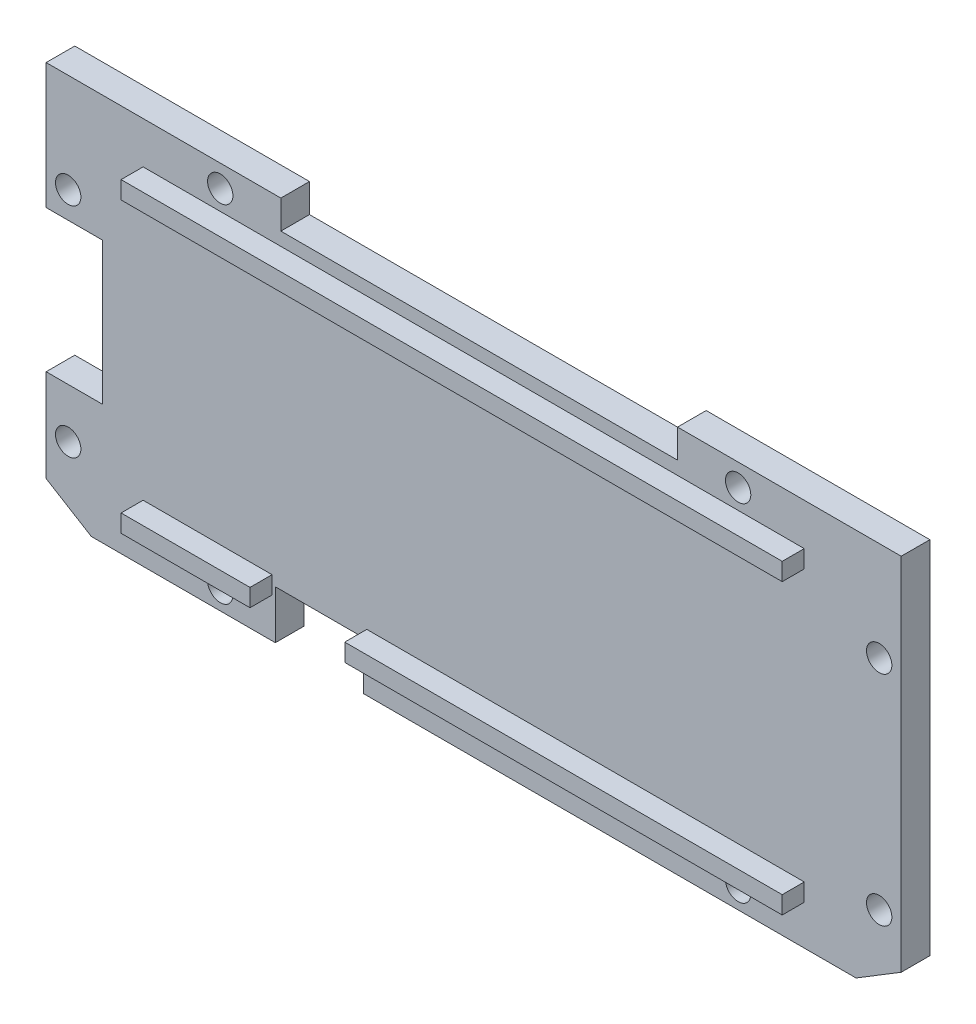
SolidWorks part; units mm, degrees
ref_plane "前视基准面" through (0, 0, 0) normal (0, 0, 1) x (1, 0, 0)
ref_plane "上视基准面" through (0, 0, 0) normal (0, 1, 0) x (1, 0, 0)
ref_plane "右视基准面" through (0, 0, 0) normal (1, 0, 0) x (0, 0, -1)
other "Configuration Table"
sketch "Trimmed upper shelf - cable notch and antenna relief profile" plane through (0, 0, 0) normal (0, 0, 1) x (1, 0, 0)
  line L0 (-38.8, -21.5) -> (-34.7, -24)
  line L1 (-34.7, -24) -> (-18, -24)
  line L2 (-18, -24) -> (-18, -19.6)
  line L3 (-18, -19.6) -> (-10, -19.6)
  line L4 (-10, -19.6) -> (-10, -24)
  line L5 (-10, -24) -> (34.7, -24)
  line L6 (34.7, -24) -> (38.8, -21.5)
  line L7 (38.8, -21.5) -> (38.8, 11.2)
  line L8 (38.8, 11.2) -> (18.5, 11.2)
  line L9 (18.5, 11.2) -> (18.5, 8.6)
  line L10 (18.5, 8.6) -> (-17.5, 8.6)
  line L11 (-17.5, 8.6) -> (-17.5, 11.2)
  line L12 (-17.5, 11.2) -> (-38.8, 11.2)
  line L13 (-38.8, 11.2) -> (-38.8, -0.2)
  line L14 (-38.8, -0.2) -> (-33.7, -0.2)
  line L15 (-33.7, -0.2) -> (-33.7, -13.1)
  line L16 (-33.7, -13.1) -> (-38.8, -13.1)
  line L17 (-38.8, -13.1) -> (-38.8, -21.5)
  circle A0 centre (-36.8, -17.6) radius 1.15
  circle A1 centre (36.8, -17.6) radius 1.15
  circle A2 centre (-36.8, 2.2) radius 1.15
  circle A3 centre (36.8, 2.2) radius 1.15
  circle A4 centre (-23, -22.2) radius 1.15
  circle A5 centre (24, -22.2) radius 1.15
  circle A6 centre (-23, 9.2) radius 1.15
  circle A7 centre (24, 9.2) radius 1.15
extrude "Trimmed upper shelf - cable notch and antenna relief" add sketch "Trimmed upper shelf - cable notch and antenna relief profile" along normal blind 2.6
sketch "PCB edge rests with antenna gap profile" plane through (0, 0, 0) normal (0, 0, 1) x (1, 0, 0)
  line L0 (-30, -20.4) -> (-18.3, -20.4)
  line L1 (-18.3, -20.4) -> (-18.3, -18.8)
  line L2 (-18.3, -18.8) -> (-30, -18.8)
  line L3 (-30, -18.8) -> (-30, -20.4)
  line L4 (-9.7, -20.4) -> (30, -20.4)
  line L5 (30, -20.4) -> (30, -18.8)
  line L6 (30, -18.8) -> (-9.7, -18.8)
  line L7 (-9.7, -18.8) -> (-9.7, -20.4)
  line L8 (-30, 5.8) -> (30, 5.8)
  line L9 (30, 5.8) -> (30, 7.4)
  line L10 (30, 7.4) -> (-30, 7.4)
  line L11 (-30, 7.4) -> (-30, 5.8)
extrude "PCB edge rests with antenna gap" add sketch "PCB edge rests with antenna gap profile" along normal blind 2 from offset 2.6
